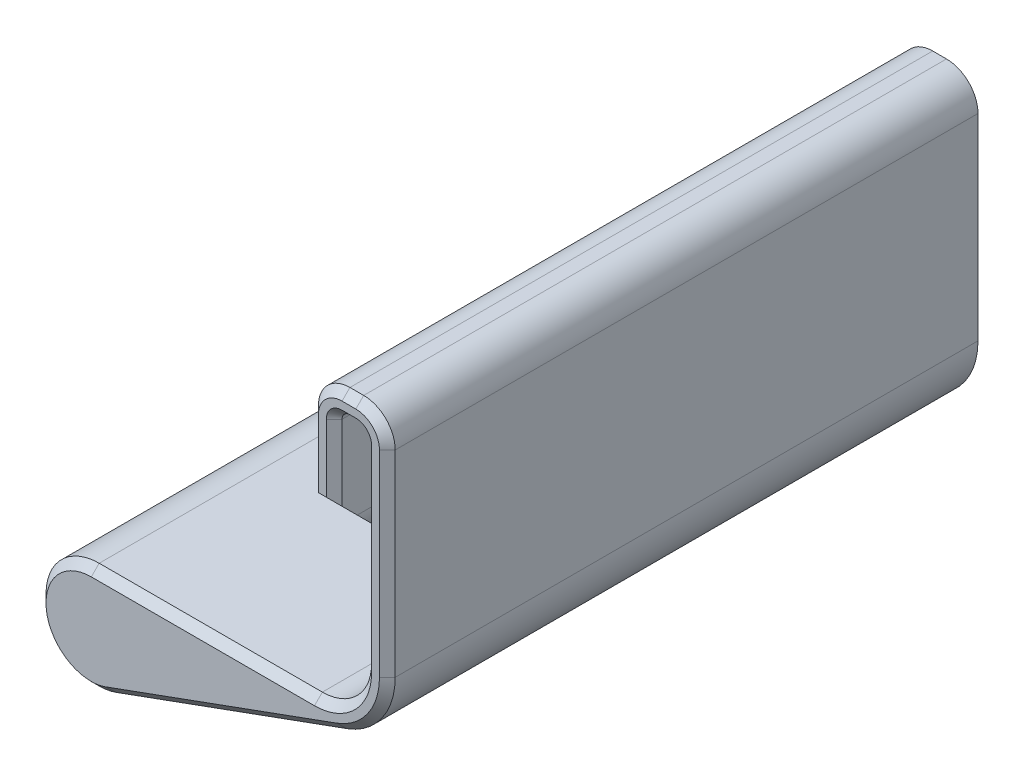
SolidWorks part; units mm, degrees
ref_plane "Front Plane" through (0, 0, 0) normal (0, 0, 1) x (1, 0, 0)
ref_plane "Top Plane" through (0, 0, 0) normal (0, 1, 0) x (1, 0, 0)
ref_plane "Right Plane" through (0, 0, 0) normal (1, 0, 0) x (0, 0, -1)
sketch "Sketch1" plane through (0, 0, 0) normal (0, 0, 1) x (1, 0, 0)
  line L0 (0, 0) -> (2.4, 0) construction
  line L1 (2.4, 0) -> (2.4, 9.2)
  line L2 (0, 0) -> (0, 9.2)
  line L3 (3.2, 10) -> (4.6, 10)
  line L4 (3.2, 12.4) -> (4.6, 12.4)
  line L5 (5.4, 9.2) -> (5.4, -10.8)
  line L6 (7.8, 9.2) -> (7.8, -10.8)
  line L7 (5.4, 9.2) -> (7.8, 9.2) construction
  line L8 (3.9, 10) -> (3.9, 12.4) construction
  line L9 (2.9309, -17.7537) -> (-20.5614, -26.3042)
  line L10 (0.4, -15.8) -> (-22.2715, -15.8)
  line L11 (-3.2971, -3.9598) -> (-0.4686, -1.1314)
  line L12 (-3.2971, -3.9598) -> (-1.6, -5.6569)
  line L13 (-1.6, -5.6569) -> (1.2284, -2.8284)
  arc A0 (2.4, 9.2) -> (3.2, 10) centre (3.2, 9.2) cw
  arc A1 (4.6, 10) -> (5.4, 9.2) centre (4.6, 9.2) cw
  arc A2 (0, 9.2) -> (3.2, 12.4) centre (3.2, 9.2) cw
  arc A3 (4.6, 12.4) -> (7.8, 9.2) centre (4.6, 9.2) cw
  arc A4 (5.4, -10.8) -> (0.4, -15.8) centre (0.4, -10.8) cw
  arc A5 (7.8, -10.8) -> (2.9309, -17.7537) centre (0.4, -10.8) cw
  arc A6 (-20.5614, -26.3042) -> (-22.2715, -26.6058) centre (-22.2715, -21.6058) cw
  arc A7 (-22.2715, -15.8) -> (-22.2715, -26.6058) centre (-22.2715, -21.2029) ccw
  arc A8 (0, 0) -> (-0.4686, -1.1314) centre (-1.6, 0) cw
  arc A9 (2.4, 0) -> (1.2284, -2.8284) centre (-1.6, 0) cw
  dimension "D1" = 0.8
  dimension "D6" = 5
  dimension "D9" = 5
  dimension "D11" = 1.6
  dimension "D2" = 2.4
  dimension "D3" = 10
  dimension "D4" = 3
  dimension "D5" = 70
  dimension "D7" = 20
  dimension "D8" = 25
  dimension "D10" = 45
  dimension "D12" = 4
extrude "Boss-Extrude1" add sketch "Sketch1" along normal blind 60
chamfer "Chamfer2" distance 0.8 angle 45 20 edges at (0, 4.6, 60) (0.9373, 11.4627, 60) (3.9, 12.4, 60) (6.8627, 11.4627, 60) (7.8, -0.8, 60) (6.4617, -15.0445, 60) (-8.8152, -22.029, 60) (-21.4032, -26.5298, 60) (-27.6744, -21.2029, 60) (-10.9357, -15.8, 60) (3.9355, -14.3355, 60) (2.4, 4.6, 60) (5.4, -0.8, 60) (2.6343, 9.7657, 60) (5.1657, 9.7657, 60) (3.9, 10, 60) (-1.8828, -2.5456, 60) (-0.1218, -0.6123, 60) (-0.1858, -4.2426, 60) (2.0955, -1.5307, 60)
sketch "Sketch2" plane through (2.4, 0, 0) normal (1, 0, 0) x (0, 0, -1)
  line L0 (-60, 2.3431) -> (-52, -5.6569)
  line L1 (-52, -5.6569) -> (-60, -5.6569)
  line L2 (-60, -5.6569) -> (-60, 2.3431)
  line L3 (-59.2, -5.6569) -> (0, -5.6569) construction
  line L4 (-60, 0) -> (-60, 9.2) construction
  line L5 (0, 2.3431) -> (-8, -5.6569)
  line L6 (-8, -5.6569) -> (0, -5.6569)
  line L7 (0, -5.6569) -> (0, 2.3431)
  dimension "D1" = 8
extrude "Cut-Extrude1" cut sketch "Sketch2" against normal through all
fillet "Fillet2" radius 0.8 2 edges at (-1.6, -5.6569, 30) (-3.2971, -3.9598, 30)
